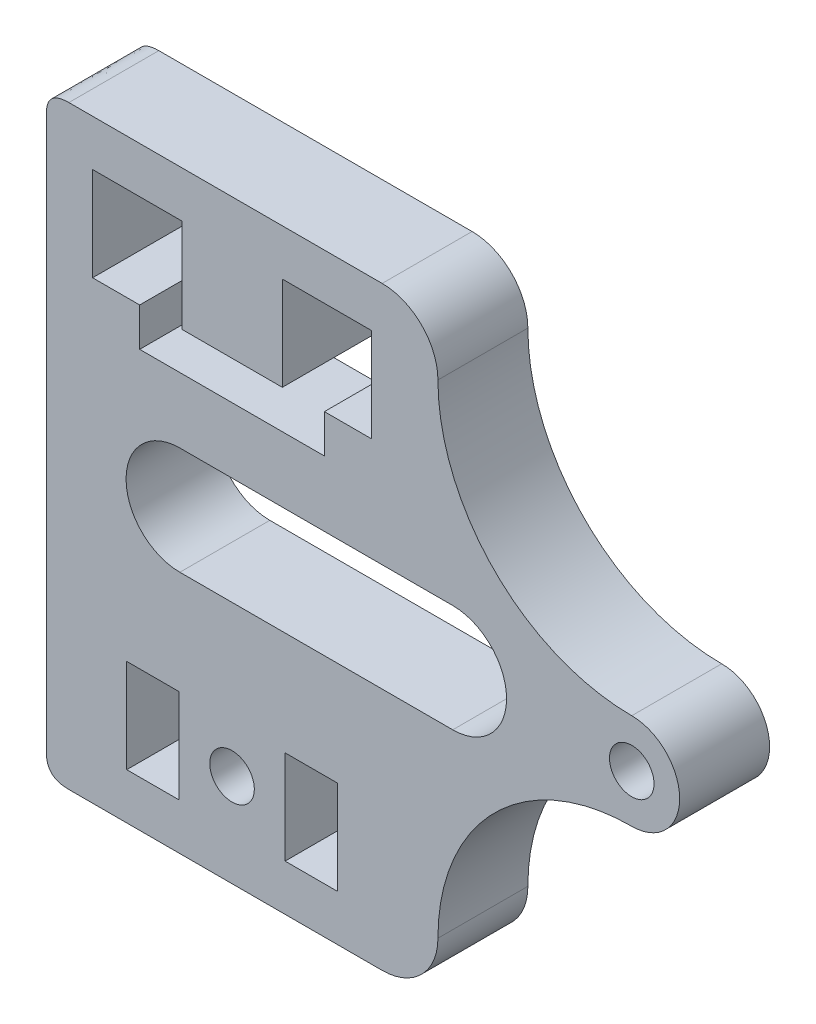
SolidWorks part; units mm, degrees
material "Acrylic (Medium-high impact)"
ref_plane "Front Plane" through (0, 0, 0) normal (0, 0, 1) x (1, 0, 0)
ref_plane "Top Plane" through (0, 0, 0) normal (0, 1, 0) x (1, 0, 0)
ref_plane "Right Plane" through (0, 0, 0) normal (1, 0, 0) x (0, 0, -1)
sketch "Sketch1" plane through (0, 0, 0) normal (0, 0, 1) x (1, 0, 0)
  line L0 (405.5669, 552.3889) -> (405.5669, 554.8889)
  line L1 (396.2885, 554.8889) -> (402.8296, 554.8889)
  line L2 (393.5512, 554.8889) -> (393.5512, 552.3889)
  line L3 (393.5512, 552.3889) -> (405.5669, 552.3889)
  line L4 (390.4885, 560.9889) -> (390.4885, 554.8889)
  line L5 (393.5512, 554.8889) -> (390.4885, 554.8889)
  line L6 (396.2885, 560.9889) -> (390.4885, 560.9889)
  line L7 (396.2885, 554.8889) -> (396.2885, 560.9889)
  line L8 (405.5669, 554.8889) -> (408.6296, 554.8889)
  line L9 (408.6296, 554.8889) -> (408.6296, 560.9889)
  line L10 (402.8296, 560.9889) -> (402.8296, 554.8889)
  line L11 (408.6296, 560.9889) -> (402.8296, 560.9889)
  line L12 (392.709, 534.3889) -> (392.709, 528.2889)
  line L13 (392.709, 528.2889) -> (396.109, 528.2889)
  line L14 (396.109, 534.3889) -> (392.709, 534.3889)
  line L15 (396.109, 528.2889) -> (396.109, 534.3889)
  line L16 (403.009, 528.2889) -> (406.4091, 528.2889)
  line L17 (406.4091, 528.2889) -> (406.4091, 534.3889)
  line L18 (403.009, 534.3889) -> (403.009, 528.2889)
  line L19 (406.4091, 534.3889) -> (403.009, 534.3889)
  line L20 (388.9465, 563.9889) -> (409.3246, 563.9889)
  line L21 (387.4885, 562.5324) -> (387.4885, 526.7454)
  line L22 (388.9465, 525.2889) -> (409.3246, 525.2889)
  line L23 (-605.591, 534.3889) -> (49394.409, 534.3889) construction
  line L24 (396.1657, 548.1389) -> (413.9157, 548.1389)
  line L25 (396.1657, 541.1389) -> (413.9157, 541.1389)
  line L26 (-600.441, 544.6389) -> (49399.559, 544.6389) construction
  line L27 (398.109, 531.3389) -> (396.109, 531.3389) construction
  line L28 (401.009, 531.3389) -> (403.009, 531.3389) construction
  line L29 (399.559, -466.6171) -> (399.559, 49533.3829) construction
  line L30 (425.559, -455.7473) -> (425.559, 49544.2527) construction
  line L31 (-608.8734, 554.8889) -> (49391.1266, 554.8889) construction
  line L32 (421.909, 544.6389) -> (421.909, 534.3889) construction
  line L33 (421.909, 544.6389) -> (421.909, 554.8889) construction
  line L34 (412.9514, 560.3621) -> (412.9514, 528.9157) construction
  circle A0 centre (425.559, 544.6389) radius 1.45
  arc A1 (396.1657, 548.1389) -> (396.1657, 541.1389) centre (396.1657, 544.6389) ccw
  circle A2 centre (399.559, 531.3389) radius 1.45
  arc A3 (412.9514, 528.9157) -> (425.559, 541.5233) centre (425.559, 528.9157) cw
  arc A4 (412.9514, 560.3621) -> (425.559, 547.7545) centre (425.559, 560.3621) ccw
  arc A5 (425.559, 547.7545) -> (425.559, 541.5233) centre (425.559, 544.6389) cw
  arc A7 (413.9157, 548.1389) -> (413.9157, 541.1389) centre (413.9157, 544.6389) cw
  arc A8 (409.3246, 525.2889) -> (412.9514, 528.9157) centre (409.3246, 528.9157) ccw
  arc A9 (409.3246, 563.9889) -> (412.9514, 560.3621) centre (409.3246, 560.3621) cw
  spline S36 degree 2 poles (387.4885, 562.5324) (387.4083, 563.9889) (388.9465, 563.9889) knots 0 0 0 1 1 1
  spline S37 degree 2 poles (387.4885, 526.7454) (387.4083, 525.2889) (388.9465, 525.2889) knots 0 0 0 1 1 1
  point P26 (399.559, 544.6389)
  point P30 (399.559, 554.8889)
  point P38 (394.409, 534.3889)
  point P40 (412.9514, 544.6389)
  dimension "D5" = 2.9
  dimension "D12" = 6.1
  dimension "D16" = 3.5
  dimension "D2" = 3.4
  dimension "D3" = 5.8
  dimension "D4" = 6.1
  dimension "D6" = 26
  dimension "D8" = 3
  dimension "D9" = 3
  dimension "D10" = 3
  dimension "D14" = 38.7
  dimension "D15" = 31.4465
  dimension "D17" = 17.75
  dimension "D19" = 13.3924
  dimension "D20" = 22.35
  dimension "D21" = 7
extrude "Boss-Extrude2" add sketch "Sketch1" along normal blind 5.85
sketch "Sketch2" plane through (0, 0, 0) normal (0, 0, 1) x (1, 0, 0)
  line L0 (-600.441, 531.3389) -> (49399.559, 531.3389) construction
  line L1 (406.4091, 528.2889) -> (406.4091, 534.3889) construction
  circle A0 centre (409.6591, 531.3389) radius 1.25
  point P5 (408.4091, 531.3389)
  dimension "D1" = 2.5
  dimension "D2" = 2
extrude "Cut-Extrude1" cut sketch "Sketch2" along normal blind 1
